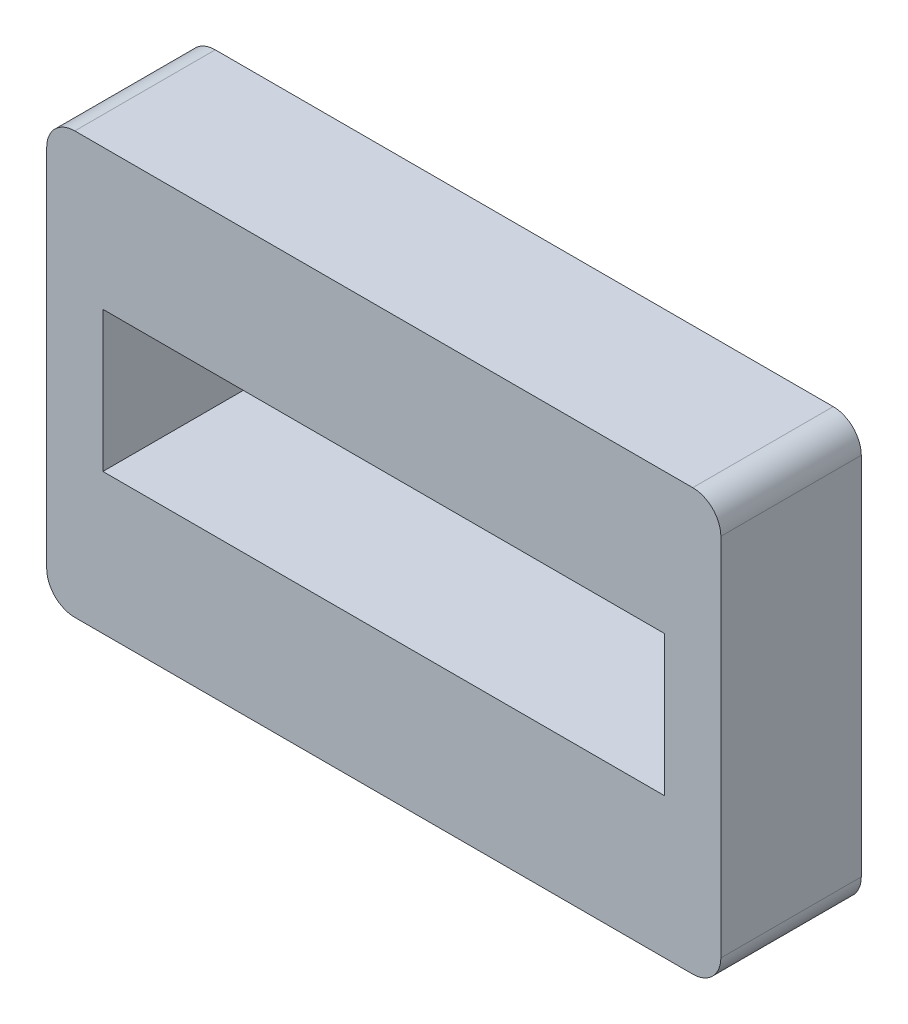
SolidWorks part; units mm, degrees
ref_plane "Front Plane" through (0, 0, 0) normal (0, 0, 1) x (1, 0, 0)
ref_plane "Top Plane" through (0, 0, 0) normal (0, 1, 0) x (1, 0, 0)
ref_plane "Right Plane" through (0, 0, 0) normal (1, 0, 0) x (0, 0, -1)
sketch "Sketch1" plane through (0, 0, 0) normal (0, 1, 0) x (1, 0, 0)
  line L1 (-12, 2.5) -> (12, 2.5)
  line L2 (-12, 2.5) -> (-12, -2.5)
  line L3 (-12, -2.5) -> (12, -2.5)
  line L4 (12, 2.5) -> (12, -2.5)
  dimension "D1" = 5
  dimension "D2" = 2.5
  dimension "D3" = 24
  dimension "D4" = 12
extrude "Boss-Extrude1" add sketch "Sketch1" along normal blind 15
sketch "Sketch2" plane through (0, 0, -2.5) normal (0, 0, -1) x (-1, 0, 0)
  line L0 (-12, 15) -> (-12, 0) construction
  line L1 (-10, 10) -> (10, 10)
  line L2 (-10, 10) -> (-10, 5)
  line L3 (-10, 5) -> (10, 5)
  line L4 (10, 10) -> (10, 5)
  line L5 (-12, 0) -> (12, 0) construction
  dimension "D1" = 5
  dimension "D2" = 20
  dimension "D3" = 2
  dimension "D4" = 5
extrude "Cut-Extrude1" cut sketch "Sketch2" against normal blind 15
fillet "Fillet2" radius 1 4 edges at (12, 0, 0) (-12, 0, 0) (-12, 15, 0) (12, 15, 0)
